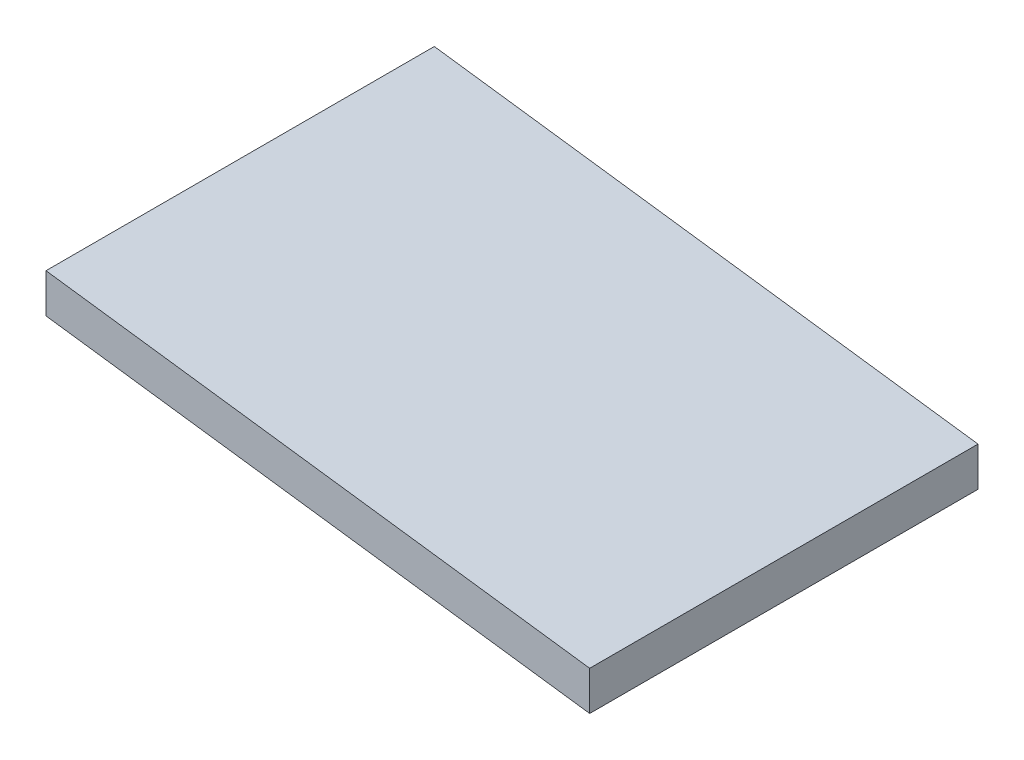
SolidWorks part; units mm, degrees
ref_plane "Ön Düzlem" through (0, 0, 0) normal (0, 0, 1) x (1, 0, 0)
ref_plane "Üst Düzlem" through (0, 0, 0) normal (0, 1, 0) x (1, 0, 0)
ref_plane "Sağ Düzlem" through (0, 0, 0) normal (1, 0, 0) x (0, 0, -1)
sketch "Sketch1" plane through (0, 0, 0) normal (0, 0, 1) x (1, 0, 0)
  line L0 (0, 0) -> (140, -18.6667)
  line L1 (140, -18.6667) -> (140, -28.7552)
  line L3 (140, -28.7552) -> (0, -10.0885)
  line L5 (0, -10.0885) -> (0, 0)
  dimension "D1" = 10
  dimension "D2" = 140
extrude "Boss-Extrude1" add sketch "Sketch1" along normal blind 100
sketch "Sketch3" plane through (0, 0, 0) normal (0.1322, 0.9912, 0) x (0.9912, -0.1322, 0)
  line L0 (0, -50) -> (141.239, -50) construction
  line L1 (0, -100) -> (0, 0) construction
  line L2 (141.239, -100) -> (141.239, 0) construction
sketch "Sketch4" plane through (0, 0, 0) normal (0.1322, 0.9912, 0) x (0.9912, -0.1322, 0)
  line L0 (141.239, -50) -> (0, -50) construction
  line L1 (141.239, -100) -> (141.239, 0) construction
  line L2 (0, -100) -> (0, 0) construction
